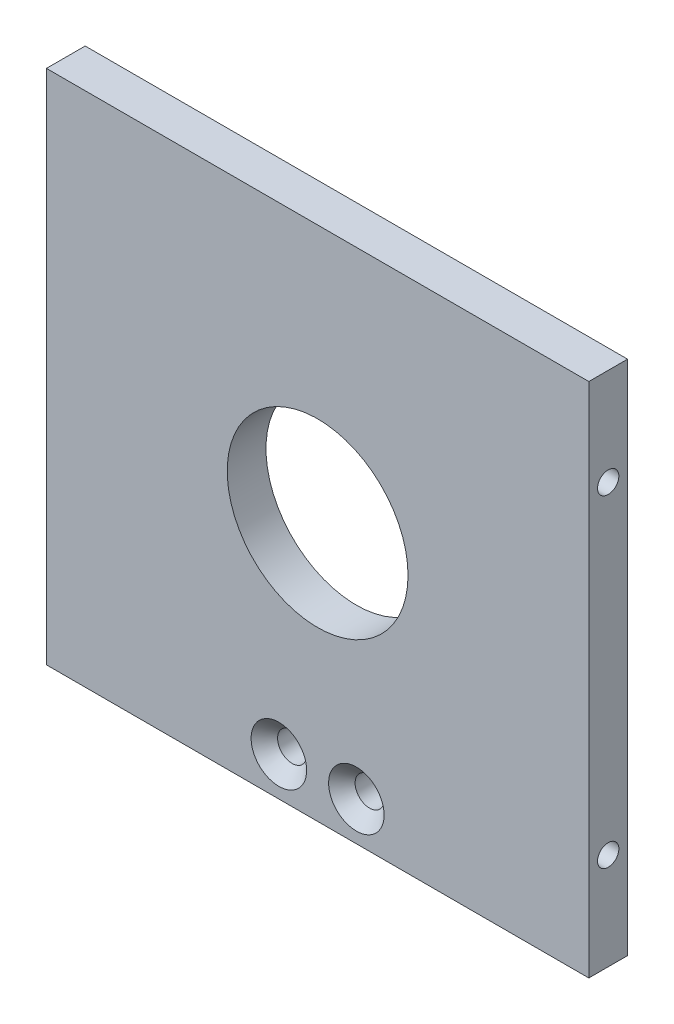
SolidWorks part; units mm, degrees
material "普通碳钢"
ref_plane "前视基准面" through (0, 0, 0) normal (0, 0, 1) x (1, 0, 0)
ref_plane "上视基准面" through (0, 0, 0) normal (0, 1, 0) x (1, 0, 0)
ref_plane "右视基准面" through (0, 0, 0) normal (1, 0, 0) x (0, 0, -1)
sketch "草图1" plane through (0, 0, 0) normal (0, 0, 1) x (1, 0, 0)
  line L1 (-42, -40) -> (42, -40)
  line L2 (-42, -40) -> (-42, 40)
  line L3 (-42, 40) -> (42, 40)
  line L4 (42, -40) -> (42, 40)
  line L5 (-42, -40) -> (42, 40) construction
  line L6 (-42, 40) -> (42, -40) construction
  circle A0 centre (0, 0) radius 14
  point P0 (0, 0)
  dimension "D3" = 28
  dimension "D1" = 84
  dimension "D2" = 80
extrude "凸台-拉伸1" add sketch "草图1" along normal mid plane 6
sketch "草图2" plane through (0, 0, 3) normal (0, 0, 1) x (1, 0, 0)
  circle A0 centre (0, 0) radius 35.75
  dimension "D1" = 71.5
extrude "切除-拉伸1" [suppressed] cut sketch "草图2" against normal blind 3
sketch "草图3" [suppressed] plane through (0, 0, 2) normal (0, 0, 1) x (1, 0, 0)
  circle A0 centre (0, 0) radius 15
  dimension "D1" = 30
extrude "切除-拉伸2" [suppressed] cut sketch "草图3" against normal blind 3
hole_wizard "M4 螺纹孔1" positions "草图5" profile "草图4" tap size "M4" standard "GB"
sketch "草图5" plane through (-42, 0, 0) normal (-1, 0, 0) x (0, 0, 1)
  line L0 (0, 0) -> (0, 42.2367) construction
  line L1 (0, 0) -> (-24.5511, 0) construction
  point P0 (0, 25)
  point P12 (0, -25)
  dimension "D1" = 50
sketch "草图4" plane through (-42, 25, 0) normal (0, 1, 0) x (0, 0, 1)
  line L0 (0, 0) -> (0, 12.4914)
  line L1 (0, 12.4914) -> (1.65, 11.5)
  line L2 (1.65, 11.5) -> (1.65, 0)
  line L5 (1.65, 0) -> (0, 0)
  line L10 (0, 12.4914) -> (-1.65, 11.5) construction
  line L11 (0, -6.35) -> (0, 107.95) construction
  dimension "螺纹孔钻头直径" = 3.3
  dimension "螺纹孔钻头深度" = 11.5
  dimension "导头角度" = 118
cosmetic thread "孔螺蚊线1" parameters "D1"=8, "D2"=4
cosmetic thread "孔螺蚊线2" parameters "D1"=8, "D2"=4
mirror "镜向1" about plane through (0, 0, 0) normal (1, 0, 0) of "M4 螺纹孔1"
hole_wizard "打孔尺寸(%根据十字)槽沉头木螺钉的类型1" positions "草图7" profile "草图6" countersink size "M4" standard "GB"
sketch "草图7" plane through (0, 0, 3) normal (0, 0, -1) x (-1, 0, 0)
  line L0 (0, 0) -> (0, -45.4755) construction
  line L1 (42, -40) -> (-42, -40) construction
  point P0 (6, -34)
  point P13 (-6, -34)
  dimension "D1" = 12
  dimension "D2" = 6
sketch "草图6" plane through (-6, -34, 3) normal (1, 0, 0) x (0, -1, 0)
  line L0 (0, 0) -> (0, 11.3519)
  line L1 (0, 11.3519) -> (2.25, 10)
  line L2 (2.25, 10) -> (2.25, 2.05)
  line L3 (2.25, 2.05) -> (4.3, 0)
  line L5 (4.3, 0) -> (0, 0)
  line L6 (-2.25, 2.05) -> (-4.3, 0) construction
  line L10 (0, 11.3519) -> (-2.25, 10) construction
  line L11 (0, -6.35) -> (0, 107.95) construction
  dimension "孔直径" = 4.5
  dimension "孔深度" = 10
  dimension "近端锥形沉头孔直径" = 8.6
  dimension "近端锥形沉头孔角度" = 90
  dimension "导头角度" = 118
